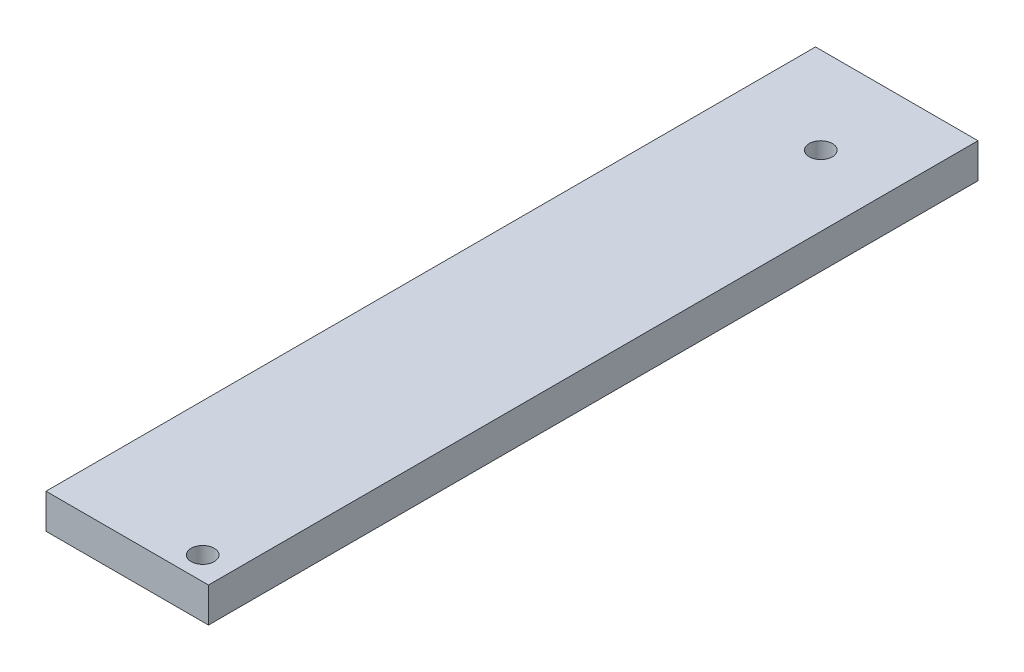
SolidWorks part; units mm, degrees
ref_plane "前视" through (0, 0, 0) normal (0, 0, 1) x (1, 0, 0)
ref_plane "上视" through (0, 0, 0) normal (0, 1, 0) x (1, 0, 0)
ref_plane "右视" through (0, 0, 0) normal (1, 0, 0) x (0, 0, -1)
sketch "Sketch1" plane through (0, 0, 0) normal (0, 1, 0) x (1, 0, 0)
  line L1 (-16.3962, 61.6054) -> (11.6838, 61.6054)
  line L2 (-16.3962, 61.6054) -> (-16.3962, -71.3946)
  line L3 (-16.3962, -71.3946) -> (11.6838, -71.3946)
  line L4 (11.6838, 61.6054) -> (11.6838, -71.3946)
  dimension "D1" = 133
  dimension "D2" = 28.08
extrude "Boss-Extrude1" add sketch "Sketch1" along normal blind 6
sketch "Sketch2" plane through (0, 6, 0) normal (0, 1, 0) x (1, 0, 0)
  line L1 (-16.3962, 61.6054) -> (11.6838, 61.6054) construction
  line L3 (11.6838, 61.6054) -> (11.6838, -71.3946) construction
  circle A1 centre (-0.4862, 46.6054) radius 2
  dimension "D3" = 4
  dimension "D4" = 15
  dimension "D6" = 12.17
extrude "Cut-Extrude1" cut sketch "Sketch2" against normal through all
sketch "Sketch3" plane through (0, 0, 0) normal (0, -1, 0) x (1, 0, 0)
  circle A0 centre (6.6838, 67.3946) radius 2 construction
  circle A1 centre (6.6838, 67.3946) radius 2
extrude "Cut-Extrude2" cut sketch "Sketch3" against normal through all contours A1
